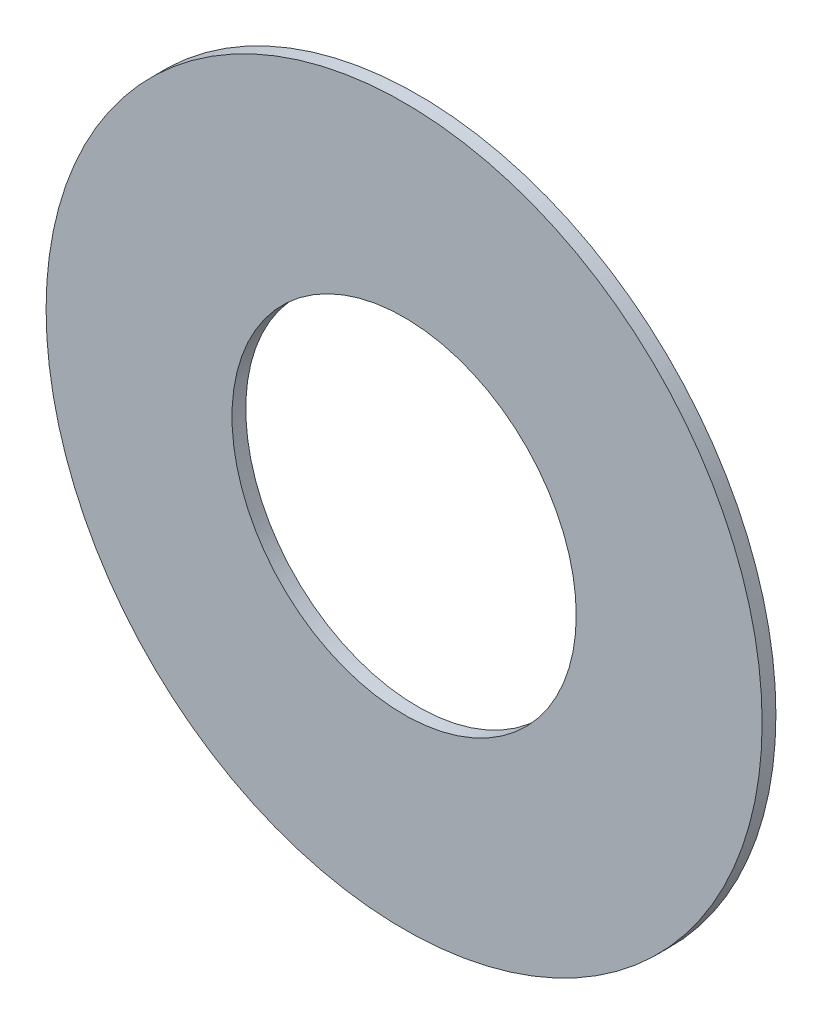
SolidWorks part; units mm, degrees
ref_plane "Ön Düzlem" through (0, 0, 0) normal (0, 0, 1) x (1, 0, 0)
ref_plane "Üst Düzlem" through (0, 0, 0) normal (0, 1, 0) x (1, 0, 0)
ref_plane "Sağ Düzlem" through (0, 0, 0) normal (1, 0, 0) x (0, 0, -1)
sketch "Çizim1" plane through (0, 0, 0) normal (0, 0, 1) x (1, 0, 0)
  circle A0 centre (0, 0) radius 12.5
  circle A1 centre (0, 0) radius 26
  dimension "D1" = 25
  dimension "D2" = 52
extrude "Yükseklik-Ekstrüzyon1" add sketch "Çizim1" along normal blind 1
